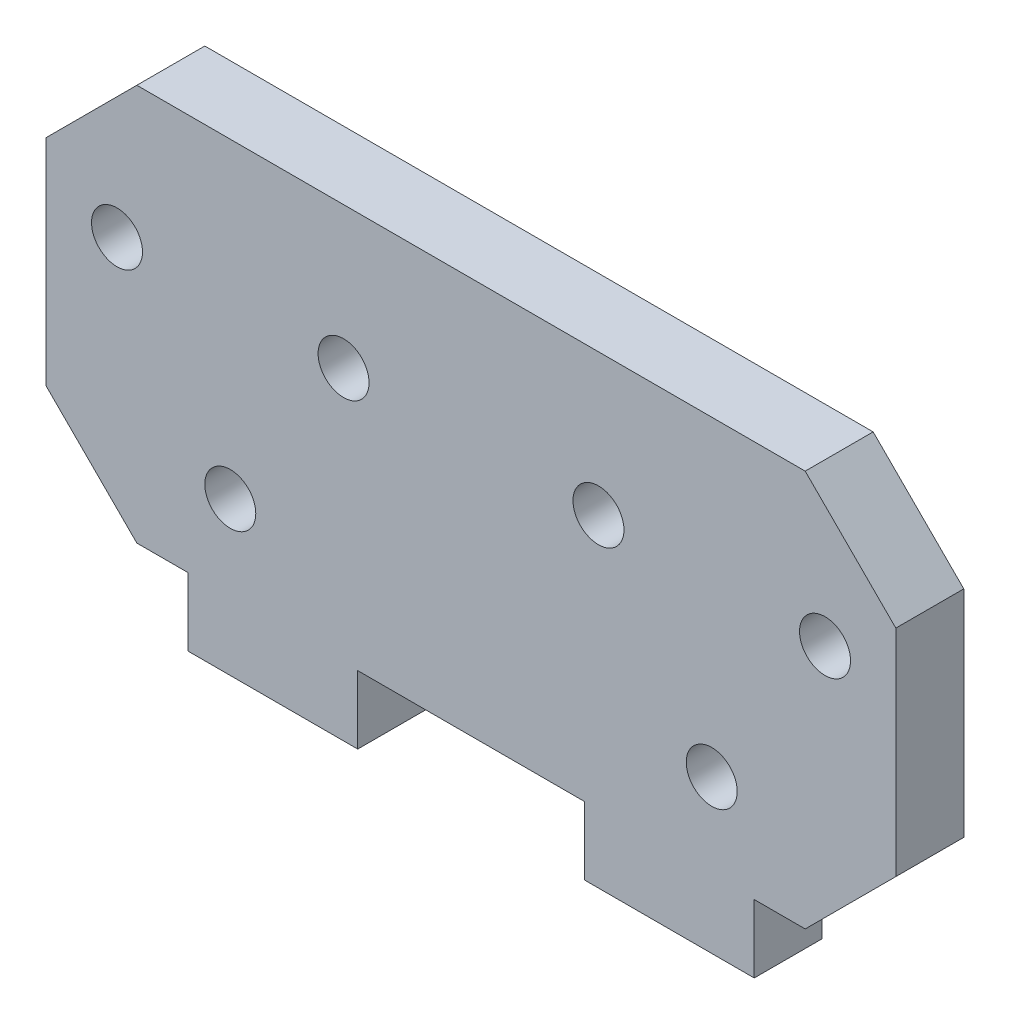
SolidWorks part; units mm, degrees
material "6061-T6 (SS)"
ref_plane "Alzado" through (0, 0, 0) normal (0, 0, 1) x (1, 0, 0)
ref_plane "Planta" through (0, 0, 0) normal (0, 1, 0) x (1, 0, 0)
ref_plane "Vista lateral" through (0, 0, 0) normal (1, 0, 0) x (0, 0, -1)
sketch "Croquis1" plane through (0, 0, 0) normal (0, 0, 1) x (1, 0, 0)
  line L0 (0, 0) -> (0, 17.5) construction
  line L2 (-37.5, 17.5) -> (37.5, 17.5)
  line L3 (-37.5, 17.5) -> (-37.5, -17.5)
  line L4 (-37.5, -17.5) -> (37.5, -17.5)
  line L5 (37.5, 17.5) -> (37.5, -17.5)
  circle A0 centre (11.25, 5) radius 11.25 construction
  arc A1 (14.6208, -0.5577) -> (7.8792, -0.5577) centre (11.25, 5) ccw construction
  circle A2 centre (-11.25, 5) radius 11.25 construction
  circle A3 centre (-11.25, 5) radius 2.25
  arc A4 (7.8792, -0.5577) -> (14.6208, -0.5577) centre (11.25, -1.5) ccw construction
  point P11 (0, 17.5)
  point P13 (37.5, 0)
  dimension "D1" = 22.5
  dimension "D2" = 13
  dimension "D6" = 4.5
  dimension "D7" = 7
  dimension "D3" = 35
  dimension "D4" = 75
  dimension "D5" = 5
extrude "Saliente-Extruir1" add sketch "Croquis1" along normal mid plane 6
hole_wizard "Taladro de margen para M41" positions "Croquis2" profile "Croquis3" hole size "M4" standard "Ansi Metric" end condition up to next
sketch "Croquis2" plane through (0, 0, 3) normal (0, 0, 1) x (1, 0, 0)
  line L0 (-31.25, 5) -> (-11.25, 5) construction
  line L2 (11.25, 5) -> (31.25, 5) construction
  circle A1 centre (-11.25, 5) radius 2.25 construction
  arc A2 (14.6208, -0.5577) -> (7.8792, -0.5577) centre (11.25, 5) ccw construction
  point P0 (-31.25, 5)
  point P2 (31.25, 5)
  point P8 (11.25, 5)
  point P21 (-21.25, -10)
  point P24 (21.25, -10)
sketch "Croquis3" plane through (-31.25, 5, 3) normal (1, 0, 0) x (0, -1, 0)
  line L0 (0, 0) -> (0, 6)
  line L1 (0, 6) -> (2.25, 6)
  line L2 (2.25, 6) -> (2.25, 0)
  line L5 (2.25, 0) -> (0, 0)
  line L11 (0, -6.35) -> (0, 107.95) construction
  dimension "Diámetro de taladro hasta el siguiente" = 4.5
  dimension "Profundidad de taladro hasta el siguiente" = 6
sketch "Croquis6" plane through (0, 0, 3) normal (0, 0, 1) x (1, 0, 0)
  line L0 (-37.5, -17.5) -> (37.5, -17.5) construction
  line L1 (-25, -17.5) -> (-10, -17.5)
  line L2 (-25, -17.5) -> (-25, -23.5)
  line L3 (-25, -23.5) -> (-10, -23.5)
  line L4 (-10, -17.5) -> (-10, -23.5)
  line L5 (-10, -20.5) -> (10, -20.5) construction
  line L6 (10, -17.5) -> (25, -17.5)
  line L7 (10, -17.5) -> (10, -23.5)
  line L8 (10, -23.5) -> (25, -23.5)
  line L9 (25, -17.5) -> (25, -23.5)
  point P12 (0, -20.5)
  dimension "D1" = 15
  dimension "D2" = 20
  dimension "D3" = 6
extrude "Saliente-Extruir2" add sketch "Croquis6" against normal through all
chamfer "Chaflán1" distance 8 angle 45 4 edges at (37.5, 17.5, 0) (37.5, -17.5, 0) (-37.5, -17.5, 0) (-37.5, 17.5, 0)
